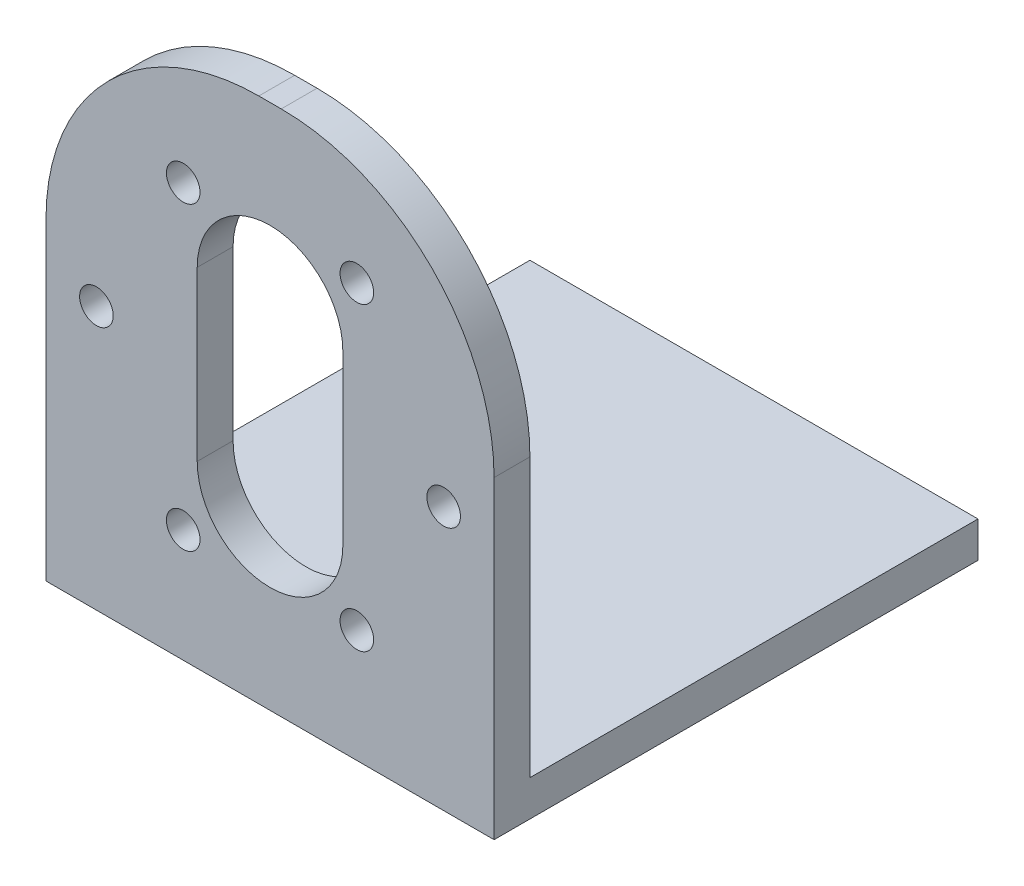
SolidWorks part; units mm, degrees
ref_plane "Alzado" through (0, 0, 0) normal (0, 0, 1) x (1, 0, 0)
ref_plane "Planta" through (0, 0, 0) normal (0, 1, 0) x (1, 0, 0)
ref_plane "Vista lateral" through (0, 0, 0) normal (1, 0, 0) x (0, 0, -1)
sketch "Croquis1" plane through (0, 0, 0) normal (0, 0, 1) x (1, 0, 0)
  line L0 (0, 16.8487) -> (0, -23.3935) construction
  line L1 (-26.4176, 0) -> (28.7714, 0) construction
  line L2 (0, 0) -> (-15.5, 0) construction
  line L3 (0, 7.5) -> (0, -7.5) construction
  line L4 (-20, -23.5) -> (20, -23.5)
  line L5 (-20, -23.5) -> (-20, 4.5)
  line L6 (-1, 23.5) -> (1, 23.5)
  line L7 (20, -23.5) -> (20, 4.5)
  line L8 (-20, -23.5) -> (20, 23.5) construction
  line L9 (-20, 23.5) -> (20, -23.5) construction
  line L10 (6.5, 7.5) -> (6.5, -7.5)
  line L11 (-6.5, 7.5) -> (-6.5, -7.5)
  line L12 (0, -14) -> (47.6072, -14) construction
  circle A0 centre (-15.5, 0) radius 1.5
  circle A1 centre (-7.75, 13.4234) radius 1.5
  circle A2 centre (7.75, 13.4234) radius 1.5
  circle A3 centre (15.5, 0) radius 1.5
  circle A4 centre (7.75, -13.4234) radius 1.5
  circle A5 centre (-7.75, -13.4234) radius 1.5
  arc A6 (1, 23.5) -> (20, 4.5) centre (1, 4.5) cw
  arc A7 (-20, 4.5) -> (-1, 23.5) centre (-1, 4.5) cw
  arc A8 (6.5, 7.5) -> (-6.5, 7.5) centre (0, 7.5) ccw
  arc A9 (-6.5, -7.5) -> (6.5, -7.5) centre (0, -7.5) ccw
  point P30 (0, 0)
  point P36 (47.6072, -10.1478)
  dimension "D1" = 3
  dimension "D6" = 19
  dimension "D8" = 14
  dimension "D2" = 47
  dimension "D4" = 15.5
  dimension "D5" = 40
  dimension "D7" = 13
  dimension "D3" = 6
extrude "Saliente-Extruir1" add sketch "Croquis1" along normal mid plane 3.2
sketch "Croquis2" plane through (0, 0, -1.6) normal (0, 0, -1) x (-1, 0, 0)
  line L0 (20, 4.5) -> (20, -23.5) construction
  line L1 (-20, -23.5) -> (20, -23.5)
  line L2 (-20, -23.5) -> (-20, -20.3)
  line L3 (-20, -20.3) -> (20, -20.3)
  line L4 (20, -23.5) -> (20, -20.3)
  dimension "D1" = 3.2
extrude "Saliente-Extruir2" add sketch "Croquis2" along normal blind 40
